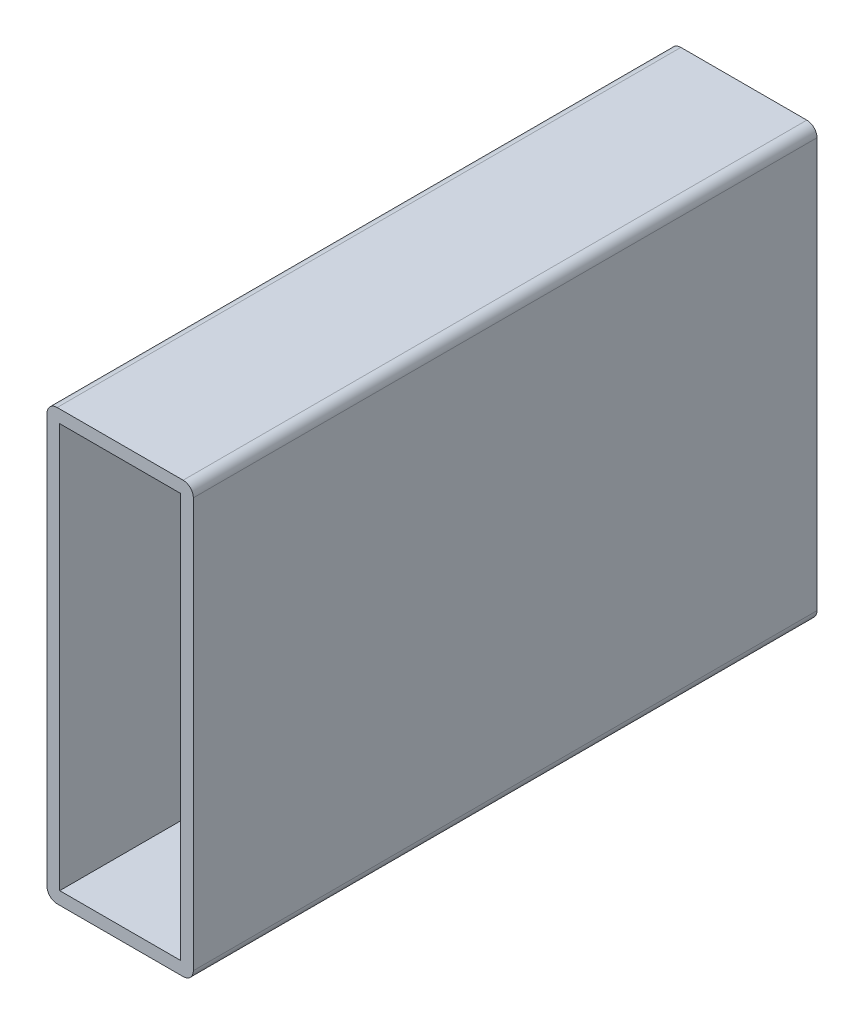
SolidWorks part; units mm, degrees
ref_plane "Front Plane" through (0, 0, 0) normal (0, 0, 1) x (1, 0, 0)
ref_plane "Top Plane" through (0, 0, 0) normal (0, 1, 0) x (1, 0, 0)
ref_plane "Right Plane" through (0, 0, 0) normal (1, 0, 0) x (0, 0, -1)
sketch "Sketch1" plane through (0, 0, 0) normal (1, 0, 0) x (0, 0, -1)
  line L1 (0, 0) -> (155.575, 0)
  line L2 (0, 0) -> (0, 107.2375)
  line L3 (0, 107.2375) -> (155.575, 107.2375)
  line L4 (155.575, 0) -> (155.575, 107.2375)
  dimension "D1" = 155.575
  dimension "D2" = 107.2375
extrude "Boss-Extrude1" add sketch "Sketch1" along normal blind 36.5
shell "Shell2" thickness 3.175
fillet "Fillet1" radius 2.54 4 edges at (36.5, 0, -77.7875) (0, 0, -77.7875) (0, 107.2375, -77.7875) (36.5, 107.2375, -77.7875)
sketch "Sketch7" plane through (0, 0, -155.575) normal (0, 0, -1) x (-1, 0, 0)
  line L1 (-13.175, 35) -> (-28.175, 35)
  line L2 (-13.175, 35) -> (-13.175, 20)
  line L3 (-13.175, 20) -> (-28.175, 20)
  line L4 (-28.175, 35) -> (-28.175, 20)
  circle A0 centre (-7.175, 30) radius 1.2 construction
  circle A1 centre (-7.175, 5) radius 1.2 construction
  circle A2 centre (-7.175, 30) radius 1.2
  circle A3 centre (-7.175, 5) radius 1.2
  dimension "D1" = 15
extrude "Cut-Extrude2" cut sketch "Sketch7" against normal up to next
sketch "Sketch8" plane through (0, 0, -152.4) normal (0, 0, 1) x (1, 0, 0)
  line L1 (33.325, 3.175) -> (3.175, 3.175) construction
  line L2 (3.175, 3.175) -> (3.175, 104.0625) construction
  circle A0 centre (7.175, 25.4) radius 2.3813
  circle A1 centre (7.175, 5) radius 1.2 construction
  circle A2 centre (7.175, 5) radius 1.2 construction
  point P2 (7.1933, 6.2324)
  point P8 (6.4538, 25.4)
  point P9 (0, 0)
  point P10 (7.175, 25.4)
  point P11 (0, 0)
  point P12 (7.175, 25.4)
  point P16 (0, 0)
  dimension "D2" = 4.7625
  dimension "D1" = 22.225
  dimension "D3" = 4
extrude "Cut-Extrude3" cut sketch "Sketch8" against normal through all
equation "\"D2@Sketch1\"=4.1875in+.875mm"
